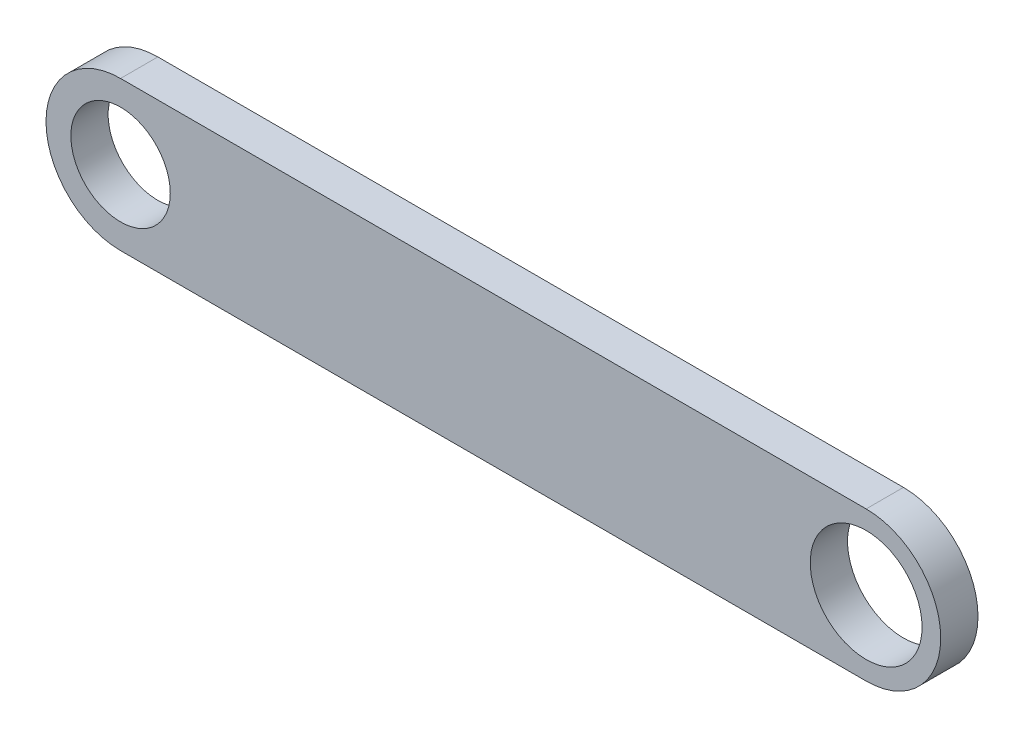
SolidWorks part; units mm, degrees
ref_plane "Front Plane" through (0, 0, 0) normal (0, 0, 1) x (1, 0, 0)
ref_plane "Top Plane" through (0, 0, 0) normal (0, 1, 0) x (1, 0, 0)
ref_plane "Right Plane" through (0, 0, 0) normal (1, 0, 0) x (0, 0, -1)
sketch "Sketch1" plane through (0, 0, 0) normal (0, 0, 1) x (1, 0, 0)
  line L0 (-83.3973, 51.3376) -> (-63.3973, 51.3376) construction
  line L1 (-83.3973, 53.3376) -> (-63.3973, 53.3376)
  line L2 (-83.3973, 49.3376) -> (-63.3973, 49.3376)
  arc A0 (-83.3973, 53.3376) -> (-83.3973, 49.3376) centre (-83.3973, 51.3376) ccw
  arc A1 (-63.3973, 49.3376) -> (-63.3973, 53.3376) centre (-63.3973, 51.3376) ccw
  circle A2 centre (-83.3973, 51.3376) radius 1.3333
  circle A3 centre (-63.3973, 51.3376) radius 1.5
  point P2 (-73.3973, 51.3376)
  dimension "D1" = 4
extrude "Boss-Extrude2" add sketch "Sketch1" along normal mid plane 1
